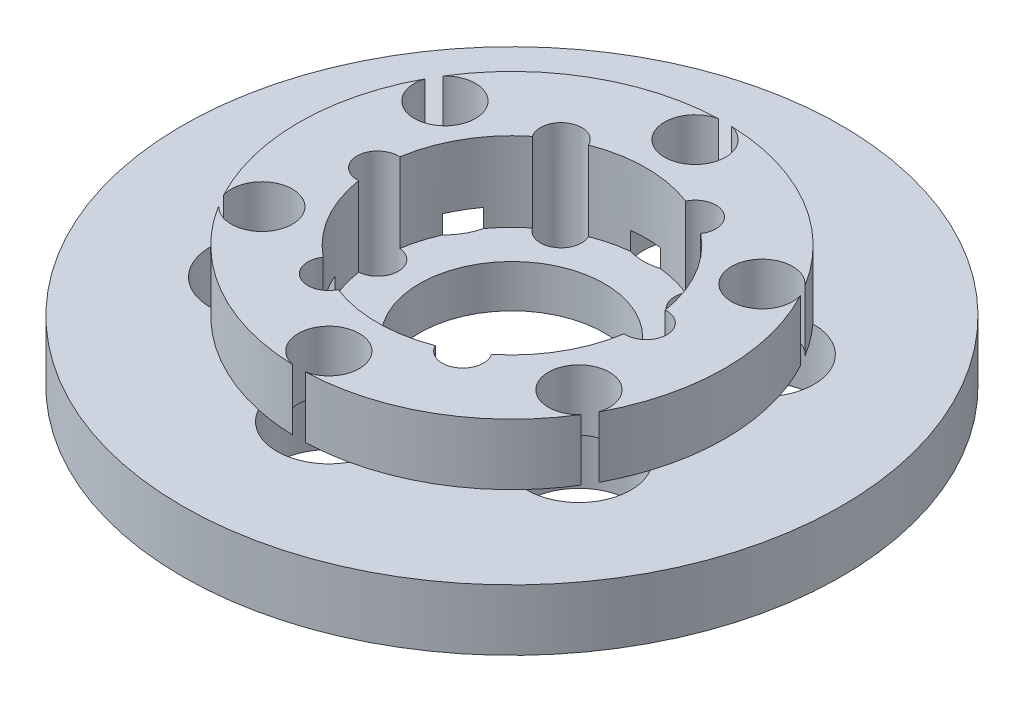
SolidWorks part; units mm, degrees
ref_plane "Front Plane" through (0, 0, 0) normal (0, 0, 1) x (1, 0, 0)
ref_plane "Top Plane" through (0, 0, 0) normal (0, 1, 0) x (1, 0, 0)
ref_plane "Right Plane" through (0, 0, 0) normal (1, 0, 0) x (0, 0, -1)
sketch "Sketch1" plane through (0, 0, 0) normal (0, 1, 0) x (1, 0, 0)
  circle A0 centre (0, 0) radius 27
  dimension "D1" = 54
extrude "Boss-Extrude1" add sketch "Sketch1" along normal blind 5
sketch "Sketch2" plane through (0, 5, 0) normal (0, 1, 0) x (1, 0, 0)
  circle A0 centre (0, 0) radius 17.45
  dimension "D1" = 34.9
extrude "Boss-Extrude2" add sketch "Sketch2" along normal blind 5
sketch "Sketch3" plane through (0, 0, 0) normal (0, -1, 0) x (1, 0, 0)
  circle A0 centre (0, 0) radius 15 construction
  circle A1 centre (0, 15) radius 2.5
  circle A2 centre (12.9904, 7.5) radius 2.5
  circle A3 centre (12.9904, -7.5) radius 2.5
  circle A4 centre (0, -15) radius 2.5
  circle A5 centre (-12.9904, -7.5) radius 2.5
  circle A6 centre (-12.9904, 7.5) radius 2.5
  point P17 (0, 0)
  dimension "D1" = 30
  dimension "D2" = 5
  dimension "D3" = 6
extrude "Cut-Extrude1" cut sketch "Sketch3" against normal blind 15
sketch "Sketch5" plane through (0, 10, 0) normal (0, 1, 0) x (1, 0, 0)
  circle A0 centre (0, 0) radius 11
  dimension "D1" = 22
extrude "Cut-Extrude2" cut sketch "Sketch5" against normal blind 6.5
sketch "Sketch6" plane through (0, 10, 0) normal (0, 1, 0) x (1, 0, 0)
  circle A0 centre (-11, 0) radius 1.6891
  circle A1 centre (0, 0) radius 11 construction
  circle A2 centre (0, 0) radius 11 construction
  circle A3 centre (-5.5, 9.5263) radius 1.6891
  circle A4 centre (5.5, 9.5263) radius 1.6891
  circle A5 centre (11, 0) radius 1.6891
  circle A6 centre (5.5, -9.5263) radius 1.6891
  circle A7 centre (-5.5, -9.5263) radius 1.6891
  point P18 (0, 0)
  dimension "D1" = 6
extrude "Cut-Extrude3" cut sketch "Sketch6" against normal blind 36.5
sketch "Sketch7" plane through (0, 3.5, 0) normal (0, 1, 0) x (1, 0, 0)
  circle A0 centre (0, 0) radius 5
  dimension "D1" = 10
extrude "Cut-Extrude4" cut sketch "Sketch7" against normal blind 36.5
sketch "Sketch8" plane through (0, 0, 0) normal (0, -1, 0) x (1, 0, 0)
  circle A0 centre (0, 15) radius 4.25
  circle A1 centre (12.9904, 7.5) radius 4.25
  circle A2 centre (12.9904, -7.5) radius 4.25
  circle A3 centre (0, -15) radius 4.25
  circle A4 centre (-12.9904, -7.5) radius 4.25
  circle A5 centre (-12.9904, 7.5) radius 4.25
  point P15 (0, 0)
  dimension "D1" = 8.5
  dimension "D2" = 6
extrude "Cut-Extrude5" cut sketch "Sketch8" against normal blind 5
sketch "Sketch10" plane through (0, 3.5, 0) normal (0, 1, 0) x (1, 0, 0)
  circle A0 centre (0, 0) radius 7.5742
extrude "Cut-Extrude6" cut sketch "Sketch10" against normal up to next
